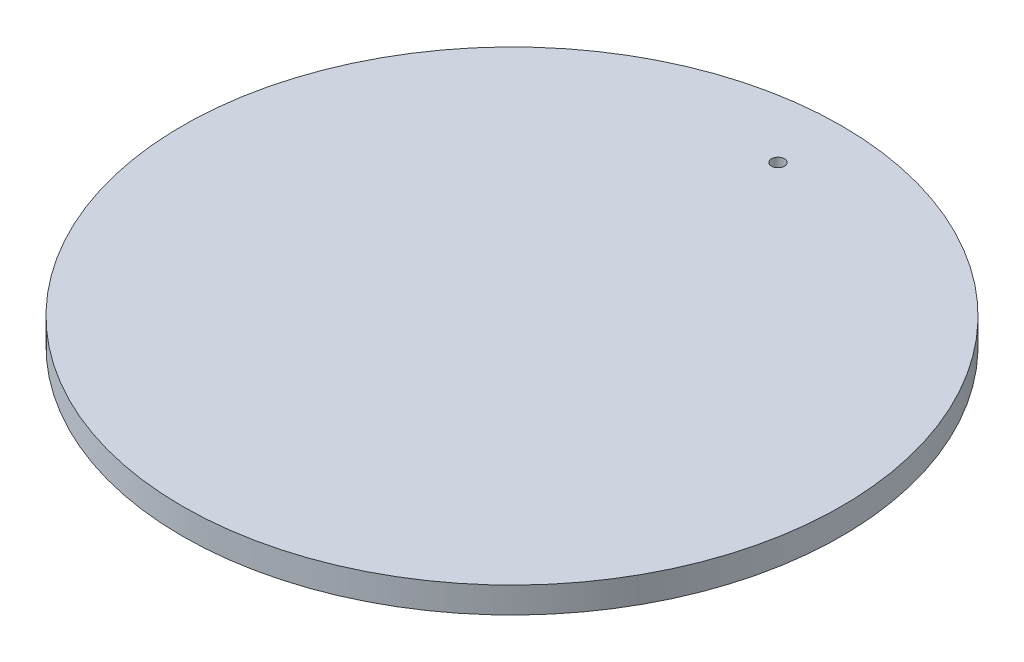
SolidWorks part; units mm, degrees
material "1060 Alloy"
ref_plane "Front Plane" through (0, 0, 0) normal (0, 0, 1) x (1, 0, 0)
ref_plane "Top Plane" through (0, 0, 0) normal (0, 1, 0) x (1, 0, 0)
ref_plane "Right Plane" through (0, 0, 0) normal (1, 0, 0) x (0, 0, -1)
sketch "Sketch1" plane through (0, 0, 0) normal (0, 1, 0) x (1, 0, 0)
  circle A0 centre (0, 0) radius 12.7
  dimension "D1" = 25.4
extrude "Boss-Extrude1" add sketch "Sketch1" along normal blind 1
sketch "Sketch4" plane through (0, 1, 0) normal (0, 1, 0) x (1, 0, 0)
  circle A0 centre (0, 10.25) radius 0.25
  dimension "D1" = 0.5
  dimension "D2" = 10.25
extrude "Cut-Extrude3" cut sketch "Sketch4" against normal through all both and the other way through all
